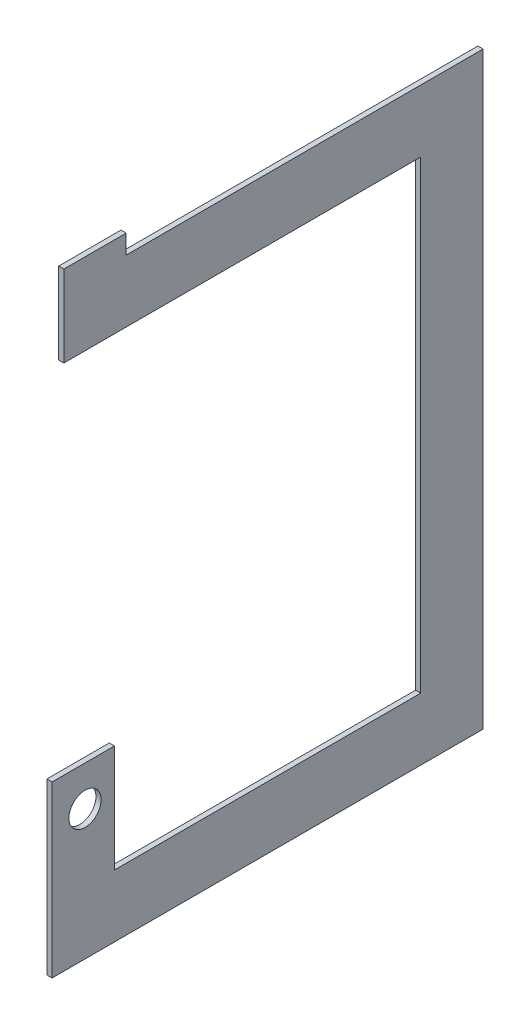
SolidWorks part; units mm, degrees
ref_plane "Front Plane" through (0, 0, 0) normal (0, 0, 1) x (1, 0, 0)
ref_plane "Top Plane" through (0, 0, 0) normal (0, 1, 0) x (1, 0, 0)
ref_plane "Right Plane" through (0, 0, 0) normal (1, 0, 0) x (0, 0, -1)
sketch "Sketch2" plane through (0, 0, 0) normal (1, 0, 0) x (0, 0, -1)
  line L0 (0, 0) -> (0, -9.8)
  line L1 (0, -9.8) -> (24.8771, -9.8)
  line L2 (24.8771, -9.8) -> (24.8771, 24.2)
  line L3 (24.8771, 24.2) -> (4.2771, 24.2)
  line L4 (4.2771, 24.2) -> (4.2771, 25.3)
  line L5 (4.2771, 25.3) -> (0.6771, 25.3)
  line L6 (0.6771, 25.3) -> (0.6771, 20.6)
  line L7 (0.6771, 20.6) -> (21.2771, 20.6)
  line L8 (21.2771, 20.6) -> (21.2771, -6.2)
  line L9 (21.2771, -6.2) -> (3.6, -6.2)
  line L10 (3.6, -6.2) -> (3.6, 0)
  line L11 (3.6, 0) -> (0, 0)
  circle A0 centre (1.9, -2.295) radius 0.93
  point P12 (10.9771, 20.6)
  dimension "D11" = 1.86
  dimension "D1" = 9.8
  dimension "D2" = 3.6
  dimension "D3" = 24.8771
  dimension "D4" = 24.2
  dimension "D5" = 3.6
  dimension "D6" = 3.6
  dimension "D7" = 3.6
  dimension "D8" = 4.7
  dimension "D9" = 3.6
  dimension "D10" = 34
  dimension "D12" = 1.7
  dimension "D13" = 2.295
extrude "Boss-Extrude1" add sketch "Sketch2" along normal blind 0.3
